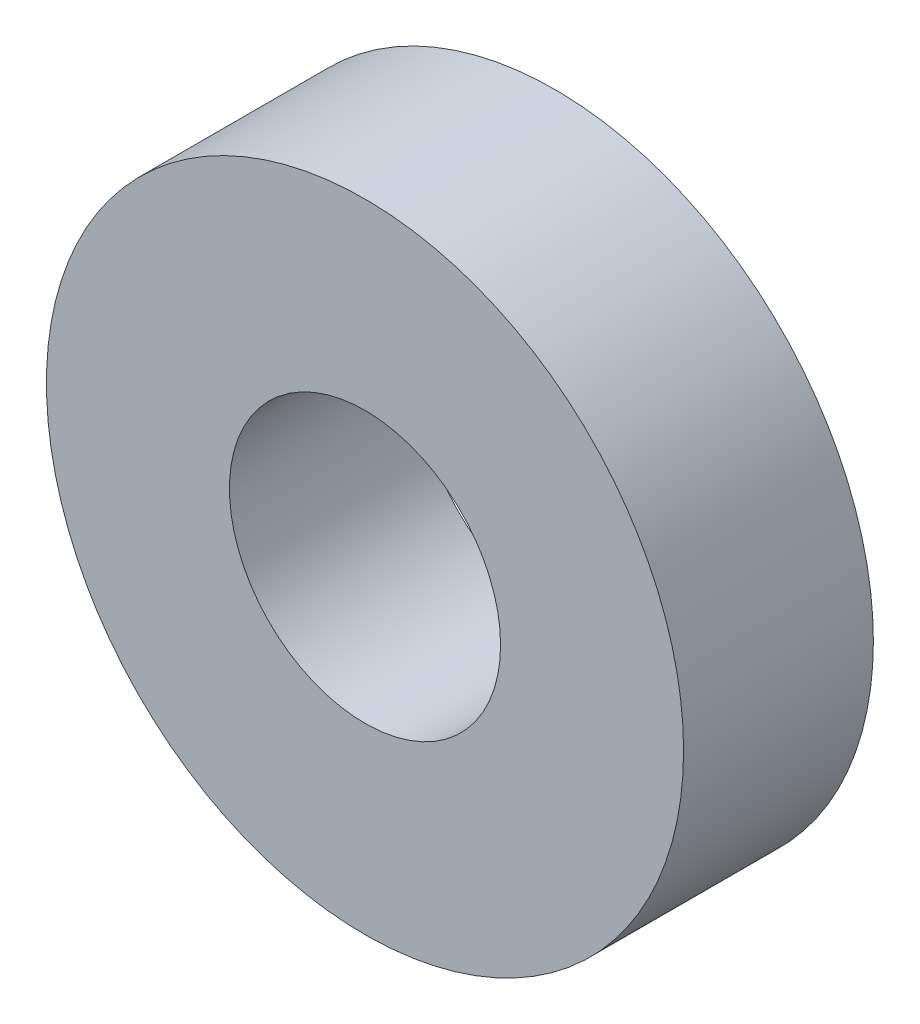
SolidWorks part; units mm, degrees
ref_plane "Спереди" through (0, 0, 0) normal (0, 0, 1) x (1, 0, 0)
ref_plane "Сверху" through (0, 0, 0) normal (0, 1, 0) x (1, 0, 0)
ref_plane "Справа" through (0, 0, 0) normal (1, 0, 0) x (0, 0, -1)
sketch "Эскиз1" plane through (0, 0, 0) normal (0, 0, 1) x (1, 0, 0)
  circle A0 centre (0, 0) radius 23.5
  circle A1 centre (0, 0) radius 10
extrude "Purchased_bearing_envelope" add sketch "Эскиз1" along normal blind 14 from offset 45
